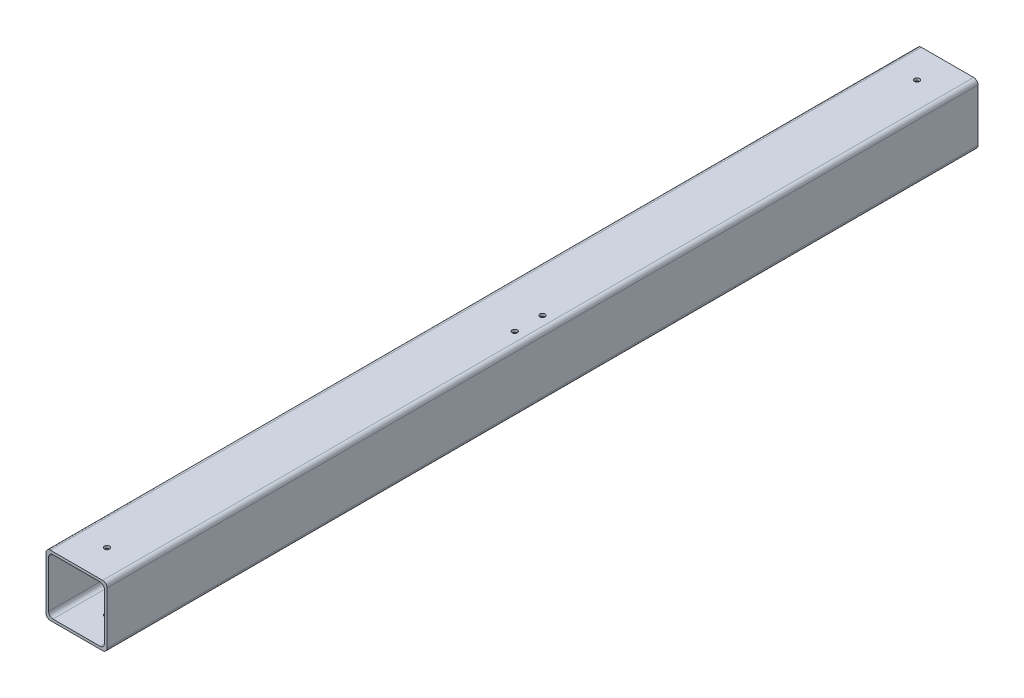
SolidWorks part; units mm, degrees
ref_plane "Front Plane" through (0, 0, 0) normal (0, 0, 1) x (1, 0, 0)
ref_plane "Top Plane" through (0, 0, 0) normal (0, 1, 0) x (1, 0, 0)
ref_plane "Right Plane" through (0, 0, 0) normal (1, 0, 0) x (0, 0, -1)
sketch "Sketch1" plane through (0, 0, 0) normal (0, 0, 1) x (1, 0, 0)
  line L0 (3, 67) -> (67, 67)
  line L1 (0, 0) -> (70, 0)
  line L2 (0, 0) -> (0, 70)
  line L3 (0, 70) -> (70, 70)
  line L4 (70, 0) -> (70, 70)
  line L5 (67, 3) -> (67, 67)
  line L6 (3, 3) -> (67, 3)
  line L7 (3, 3) -> (3, 67)
  dimension "D1" = 70
  dimension "D2" = 70
  dimension "D3" = 3
extrude "Boss-Extrude1" add sketch "Sketch1" along normal blind 1000
fillet "Fillet1" radius 5 8 edges at (67, 67, 500) (0, 70, 500) (0, 0, 500) (67, 3, 500) (70, 0, 500) (3, 3, 500) (3, 67, 500) (70, 70, 500)
sketch "Sketch2" plane through (0, 70, 0) normal (0, 1, 0) x (1, 0, 0)
  line L0 (35, 0) -> (35, -1000) construction
  line L1 (65, 0) -> (5, 0) construction
  line L2 (65, -1000) -> (5, -1000) construction
  circle A0 centre (35, -965) radius 3
  circle A1 centre (35, -35) radius 3
  dimension "D1" = 6
  dimension "D3" = 6
  dimension "D2" = 35
  dimension "D4" = 35
extrude "Cut-Extrude1" cut sketch "Sketch2" against normal blind 70
sketch "Sketch3" plane through (70, 0, 0) normal (1, 0, 0) x (0, 0, -1)
  line L0 (-1000, 70) -> (0, 70) construction
  line L2 (-1000, 5) -> (-1000, 65) construction
  circle A0 centre (-500, 35) radius 3
  dimension "D3" = 6
  dimension "D1" = 35
  dimension "D2" = 500
sketch "Sketch4" plane through (0, 0, 0) normal (0, -1, 0) x (1, 0, 0)
  line L0 (0, 500) -> (70, 500) construction
  line L1 (0, 0) -> (0, 1000) construction
  line L2 (70, 497) -> (70, 503) construction
  line L3 (70, 1000) -> (70, 0) construction
  circle A0 centre (54.09, 515.91) radius 3
  circle A1 centre (54.09, 484.09) radius 3
  dimension "D1" = 15.91
  dimension "D2" = 15.91
extrude "Cut-Extrude2" cut sketch "Sketch4" against normal blind 70 contours A0 | A1
